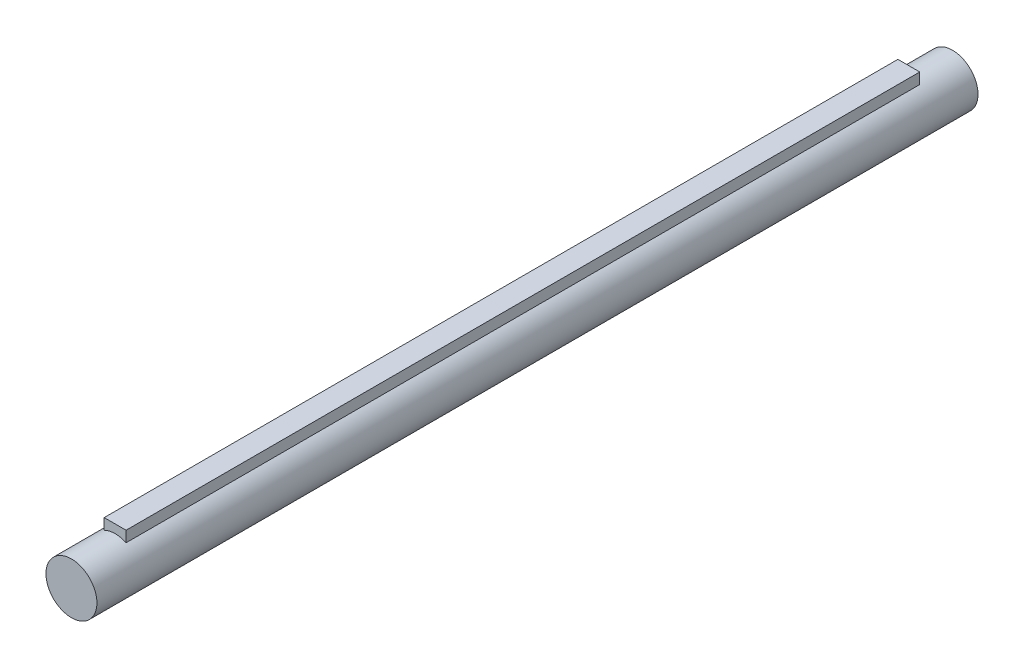
SolidWorks part; units mm, degrees
ref_plane "Plan de face" through (0, 0, 0) normal (0, 0, 1) x (1, 0, 0)
ref_plane "Plan de dessus" through (0, 0, 0) normal (0, 1, 0) x (1, 0, 0)
ref_plane "Plan de droite" through (0, 0, 0) normal (1, 0, 0) x (0, 0, -1)
sketch "Esquisse1" plane through (0, 0, 0) normal (0, 0, 1) x (1, 0, 0)
  line L0 (0, 0) -> (0, 3.1623) construction
  line L1 (-1.5, 3.1623) -> (1.5, 3.1623) construction
  line L2 (-1.5, 3.1623) -> (-1.5, 4.6623)
  line L3 (-1.5, 4.6623) -> (1.5, 4.6623)
  line L4 (1.5, 4.6623) -> (1.5, 3.1623)
  arc A0 (-1.5, 3.1623) -> (1.5, 3.1623) centre (0, 0) ccw
  point P5 (0, 3.1623)
  dimension "D1" = 3.5
  dimension "D3" = 1.5
  dimension "D2" = 3
extrude "Boss.-Extru.1" add sketch "Esquisse1" along normal blind 121
sketch "Esquisse2" plane through (0, 0, 121) normal (0, 0, 1) x (1, 0, 0)
  line L0 (-1.5, 3.1623) -> (-1.5, 4.6623)
  line L1 (-1.5, 4.6623) -> (1.5, 4.6623)
  line L2 (1.5, 4.6623) -> (1.5, 3.1623)
  line L3 (-1.5, 3.1623) -> (1.5, 3.1623) construction
  line L4 (1.5, 3.1623) -> (1.5, 4.6623) construction
  arc A3 (-1.5, 3.1623) -> (1.5, 3.1623) centre (0, 0) cw
  point P6 (0, 0)
  point P13 (-1.5, 3.1623)
  point P16 (1.5, 3.1623)
  line M8 (1.5, 3.1623) -> (1.5, 4.6623)
  line M9 (1.5, 4.6623) -> (-1.5, 4.6623)
  line M10 (-1.5, 4.6623) -> (-1.5, 3.1623)
extrude "Enlèv. mat.-Extru.1" cut sketch "Esquisse2" against normal blind 6 contours A3 M10 M8 M9
sketch "Esquisse3" plane through (0, 0, 0) normal (0, 0, -1) x (-1, 0, 0)
  line L0 (-1.5, 4.6623) -> (-1.5, 3.1623) construction
  line L1 (1.5, 4.6623) -> (-1.5, 4.6623) construction
  line L2 (1.5, 3.1623) -> (1.5, 4.6623) construction
  line L3 (-1.5, 4.6623) -> (-1.5, 3.1623)
  line L4 (1.5, 4.6623) -> (-1.5, 4.6623)
  line L5 (1.5, 3.1623) -> (1.5, 4.6623)
  arc A0 (1.5, 3.1623) -> (-1.5, 3.1623) centre (0, 0) ccw construction
  arc A1 (1.5, 3.1623) -> (-1.5, 3.1623) centre (0, 0) ccw
extrude "Enlèv. mat.-Extru.2" cut sketch "Esquisse3" against normal blind 6
